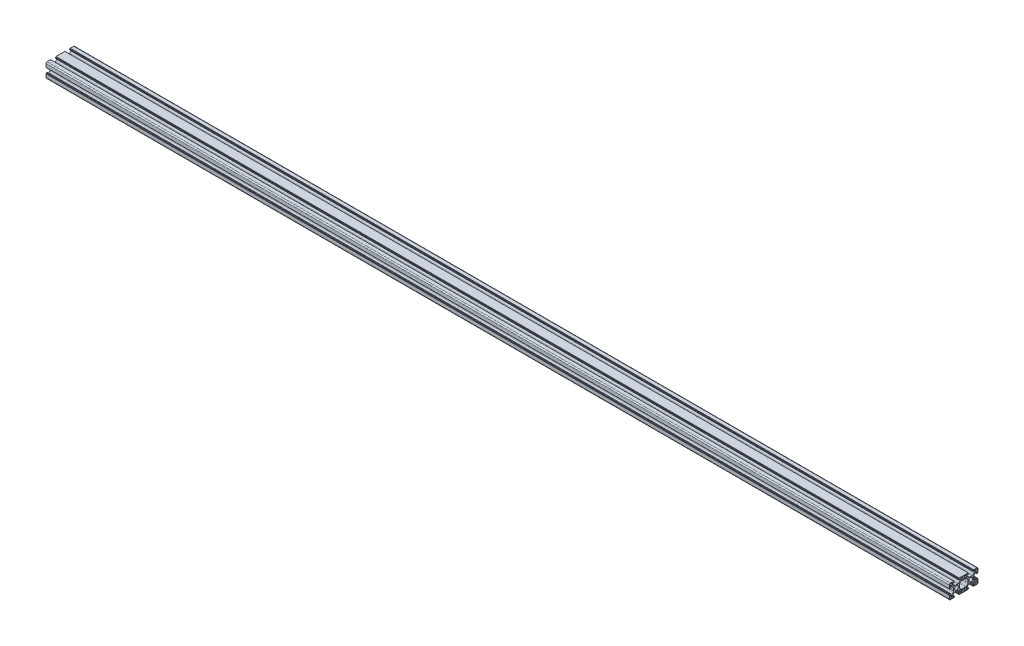
SolidWorks part; units mm, degrees
ref_plane "Спереди" through (0, 0, 0) normal (0, 0, 1) x (1, 0, 0)
ref_plane "Сверху" through (0, 0, 0) normal (0, 1, 0) x (1, 0, 0)
ref_plane "Справа" through (0, 0, 0) normal (1, 0, 0) x (0, 0, -1)
sketch "Эскиз1" plane through (0, 0, 0) normal (1, 0, 0) x (0, 0, -1)
  line L0 (-3.1522, 8.2837) -> (-1.6522, 6.7837) construction
  line L1 (18.3478, 9.7837) -> (15.3478, 6.7837) construction
  line L2 (-10.7522, 0.6837) -> (-0.7522, 10.6837) construction
  line L3 (9.2478, 4.6837) -> (11.1466, 4.6837)
  line L4 (9.2478, 0.6837) -> (19.2478, 10.6837) construction
  line L5 (16.8478, 8.2837) -> (15.3478, 9.7837) construction
  line L6 (12.5608, 5.2695) -> (13.862, 6.5707)
  line L7 (16.1478, 6.7837) -> (17.5478, 6.7837)
  line L8 (15.3478, 7.5837) -> (15.3478, 8.9837)
  line L9 (17.5478, 9.7837) -> (16.1478, 9.7837)
  line L10 (14.4478, 8.8837) -> (14.4478, 7.9849)
  line L11 (13.011, 8.757) -> (13.4914, 9.2373)
  line L12 (12.4478, 10.2328) -> (12.9478, 10.2328)
  line L13 (12.8343, 8.6837) -> (12.5478, 8.6837)
  line L14 (13.8449, 9.3837) -> (13.9478, 9.3837)
  line L15 (12.9478, 10.5337) -> (12.9478, 10.2328)
  line L16 (12.2978, 10.0828) -> (12.2978, 8.9337)
  line L17 (17.7478, 10.6837) -> (13.0978, 10.6837)
  line L18 (18.3478, 8.9837) -> (18.3478, 7.5837)
  line L19 (19.2478, 9.1837) -> (19.2478, 4.5337)
  line L20 (18.6469, 3.7337) -> (17.4978, 3.7337)
  line L21 (19.0978, 4.3837) -> (18.7969, 4.3837)
  line L22 (17.9478, 5.2808) -> (17.9478, 5.3837)
  line L23 (17.2478, 4.2702) -> (17.2478, 3.9837)
  line L24 (18.7969, 3.8837) -> (18.7969, 4.3837)
  line L25 (17.321, 4.447) -> (17.8014, 4.9273)
  line L26 (17.4478, 5.8837) -> (16.549, 5.8837)
  line L27 (13.8336, 3.9967) -> (15.1348, 5.2979)
  line L28 (13.2478, 0.6837) -> (13.2478, 2.5825)
  line L29 (13.2478, 0.6837) -> (13.2478, -1.2151)
  line L30 (13.8336, -2.6293) -> (15.1348, -3.9305)
  line L31 (15.3478, -6.2163) -> (15.3478, -7.6163)
  line L32 (16.1478, -5.4163) -> (17.5478, -5.4163)
  line L33 (18.3478, -7.6163) -> (18.3478, -6.2163)
  line L34 (17.4478, -4.5163) -> (16.549, -4.5163)
  line L35 (17.321, -3.0795) -> (17.8014, -3.5598)
  line L36 (18.7969, -2.5163) -> (18.7969, -3.0163)
  line L37 (17.2478, -2.9027) -> (17.2478, -2.6163)
  line L38 (17.9478, -3.9134) -> (17.9478, -4.0163)
  line L39 (19.0978, -3.0163) -> (18.7969, -3.0163)
  line L40 (18.6469, -2.3663) -> (17.4978, -2.3663)
  line L41 (19.2478, -7.8163) -> (19.2478, -3.1663)
  line L42 (17.5478, -8.4163) -> (16.1478, -8.4163)
  line L43 (17.7478, -9.3163) -> (13.0978, -9.3163)
  line L44 (12.2978, -8.7153) -> (12.2978, -7.5663)
  line L45 (12.9478, -9.1663) -> (12.9478, -8.8653)
  line L46 (13.8449, -8.0163) -> (13.9478, -8.0163)
  line L47 (12.8343, -7.3163) -> (12.5478, -7.3163)
  line L48 (12.4478, -8.8653) -> (12.9478, -8.8653)
  line L49 (13.011, -7.3895) -> (13.4914, -7.8698)
  line L50 (14.4478, -7.5163) -> (14.4478, -6.6175)
  line L51 (12.5608, -3.9021) -> (13.862, -5.2033)
  line L52 (9.2478, -3.3163) -> (11.1466, -3.3163)
  line L53 (18.3478, -8.4163) -> (15.3478, -5.4163) construction
  line L54 (9.2478, 0.6837) -> (19.2478, -9.3163) construction
  line L55 (16.8478, -6.9163) -> (18.3478, -5.4163) construction
  line L56 (9.2478, -3.3163) -> (7.349, -3.3163)
  line L57 (5.9348, -3.9021) -> (4.6336, -5.2033)
  line L58 (2.3478, -5.4163) -> (0.9478, -5.4163)
  line L59 (3.1478, -6.2163) -> (3.1478, -7.6163)
  line L60 (0.9478, -8.4163) -> (2.3478, -8.4163)
  line L61 (4.0478, -7.5163) -> (4.0478, -6.6175)
  line L62 (5.4846, -7.3895) -> (5.0043, -7.8698)
  line L63 (6.0478, -8.8653) -> (5.5478, -8.8653)
  line L64 (5.6614, -7.3163) -> (5.9478, -7.3163)
  line L65 (4.6507, -8.0163) -> (4.5478, -8.0163)
  line L66 (5.5478, -9.1663) -> (5.5478, -8.8653)
  line L67 (6.1978, -8.7153) -> (6.1978, -7.5663)
  line L68 (0.7478, -9.3163) -> (5.3978, -9.3163)
  line L69 (0.1478, -7.6163) -> (0.1478, -6.2163)
  line L70 (1.0478, -4.5163) -> (1.9466, -4.5163)
  line L71 (4.662, -2.6293) -> (3.3608, -3.9305)
  line L72 (5.2478, 0.6837) -> (5.2478, -1.2151)
  line L73 (-1.6522, 9.7837) -> (-4.6522, 6.7837) construction
  line L74 (0.1478, -8.4163) -> (3.1478, -5.4163) construction
  line L75 (-3.1522, -6.9163) -> (-4.6522, -8.4163) construction
  line L76 (9.2478, 0.6837) -> (-0.7522, -9.3163) construction
  line L77 (1.6478, -6.9163) -> (3.1478, -8.4163) construction
  line L78 (5.2478, 0.6837) -> (5.2478, 2.5825)
  line L79 (4.662, 3.9967) -> (3.3608, 5.2979)
  line L80 (3.1478, 7.5837) -> (3.1478, 8.9837)
  line L81 (2.3478, 6.7837) -> (0.9478, 6.7837)
  line L82 (0.1478, 8.9837) -> (0.1478, 7.5837)
  line L83 (1.0478, 5.8837) -> (1.9466, 5.8837)
  line L84 (0.9478, 9.7837) -> (2.3478, 9.7837)
  line L85 (0.7478, 10.6837) -> (5.3978, 10.6837)
  line L86 (6.1978, 10.0828) -> (6.1978, 8.9337)
  line L87 (5.5478, 10.5337) -> (5.5478, 10.2328)
  line L88 (4.6507, 9.3837) -> (4.5478, 9.3837)
  line L89 (5.6614, 8.6837) -> (5.9478, 8.6837)
  line L90 (6.0478, 10.2328) -> (5.5478, 10.2328)
  line L91 (5.4846, 8.757) -> (5.0043, 9.2373)
  line L92 (4.0478, 8.8837) -> (4.0478, 7.9849)
  line L93 (5.9348, 5.2695) -> (4.6336, 6.5707)
  line L94 (9.2478, 4.6837) -> (7.349, 4.6837)
  line L95 (-2.5162, 0.6837) -> (20.7522, 0.6837) construction
  line L96 (0.1478, 9.7837) -> (3.1478, 6.7837) construction
  line L97 (9.2478, -11.4027) -> (9.2478, 11.4027) construction
  line L98 (9.2478, 0.6837) -> (-0.7522, 10.6837) construction
  line L99 (1.6478, 8.2837) -> (0.1478, 6.7837) construction
  line L100 (-10.7522, 0.6837) -> (-0.7522, -9.3163) construction
  line L101 (-1.6522, -8.4163) -> (-4.6522, -5.4163) construction
  line L102 (-18.3522, -6.9163) -> (-19.8522, -5.4163) construction
  line L103 (-10.7522, 0.6837) -> (-20.7522, -9.3163) construction
  line L104 (-19.8522, -8.4163) -> (-16.8522, -5.4163) construction
  line L105 (-18.3522, 8.2837) -> (-16.8522, 9.7837) construction
  line L106 (-10.7522, 0.6837) -> (-20.7522, 10.6837) construction
  line L107 (-19.8522, 9.7837) -> (-16.8522, 6.7837) construction
  line L108 (-10.7522, 4.6837) -> (-8.8534, 4.6837)
  line L109 (-7.4392, 5.2695) -> (-6.138, 6.5707)
  line L110 (-5.5522, 8.8837) -> (-5.5522, 7.9849)
  line L111 (-6.989, 8.757) -> (-6.5086, 9.2373)
  line L112 (-7.5522, 10.2328) -> (-7.0522, 10.2328)
  line L113 (-7.1657, 8.6837) -> (-7.4522, 8.6837)
  line L114 (-6.1551, 9.3837) -> (-6.0522, 9.3837)
  line L115 (-7.0522, 10.5337) -> (-7.0522, 10.2328)
  line L116 (-7.7022, 10.0828) -> (-7.7022, 8.9337)
  line L117 (-2.2522, 10.6837) -> (-6.9022, 10.6837)
  line L118 (-2.4522, 9.7837) -> (-3.8522, 9.7837)
  line L119 (-2.5522, 5.8837) -> (-3.451, 5.8837)
  line L120 (-1.6522, 8.9837) -> (-1.6522, 7.5837)
  line L121 (-3.8522, 6.7837) -> (-2.4522, 6.7837)
  line L122 (-4.6522, 7.5837) -> (-4.6522, 8.9837)
  line L123 (-6.1664, 3.9967) -> (-4.8652, 5.2979)
  line L124 (-6.7522, 0.6837) -> (-6.7522, 2.5825)
  line L125 (-6.7522, 0.6837) -> (-6.7522, -1.2151)
  line L126 (-6.1664, -2.6293) -> (-4.8652, -3.9305)
  line L127 (-2.5522, -4.5163) -> (-3.451, -4.5163)
  line L128 (-1.6522, -7.6163) -> (-1.6522, -6.2163)
  line L129 (-2.2522, -9.3163) -> (-6.9022, -9.3163)
  line L130 (-7.7022, -8.7153) -> (-7.7022, -7.5663)
  line L131 (-7.0522, -9.1663) -> (-7.0522, -8.8653)
  line L132 (-6.1551, -8.0163) -> (-6.0522, -8.0163)
  line L133 (-7.1657, -7.3163) -> (-7.4522, -7.3163)
  line L134 (-7.5522, -8.8653) -> (-7.0522, -8.8653)
  line L135 (-6.989, -7.3895) -> (-6.5086, -7.8698)
  line L136 (-5.5522, -7.5163) -> (-5.5522, -6.6175)
  line L137 (-2.4522, -8.4163) -> (-3.8522, -8.4163)
  line L138 (-4.6522, -6.2163) -> (-4.6522, -7.6163)
  line L139 (-3.8522, -5.4163) -> (-2.4522, -5.4163)
  line L140 (-7.4392, -3.9021) -> (-6.138, -5.2033)
  line L141 (-10.7522, -3.3163) -> (-8.8534, -3.3163)
  line L142 (-10.7522, -3.3163) -> (-12.651, -3.3163)
  line L143 (-14.0652, -3.9021) -> (-15.3664, -5.2033)
  line L144 (-15.9522, -7.5163) -> (-15.9522, -6.6175)
  line L145 (-14.5154, -7.3895) -> (-14.9957, -7.8698)
  line L146 (-13.9522, -8.8653) -> (-14.4522, -8.8653)
  line L147 (-14.3386, -7.3163) -> (-14.0522, -7.3163)
  line L148 (-15.3493, -8.0163) -> (-15.4522, -8.0163)
  line L149 (-14.4522, -9.1663) -> (-14.4522, -8.8653)
  line L150 (-13.8022, -8.7153) -> (-13.8022, -7.5663)
  line L151 (-19.2522, -9.3163) -> (-14.6022, -9.3163)
  line L152 (-19.0522, -8.4163) -> (-17.6522, -8.4163)
  line L153 (-20.7522, -7.8163) -> (-20.7522, -3.1663)
  line L154 (-20.1512, -2.3663) -> (-19.0022, -2.3663)
  line L155 (-20.6022, -3.0163) -> (-20.3012, -3.0163)
  line L156 (-19.4522, -3.9134) -> (-19.4522, -4.0163)
  line L157 (-18.7522, -2.9027) -> (-18.7522, -2.6163)
  line L158 (-20.3012, -2.5163) -> (-20.3012, -3.0163)
  line L159 (-18.8254, -3.0795) -> (-19.3057, -3.5598)
  line L160 (-18.9522, -4.5163) -> (-18.0534, -4.5163)
  line L161 (-19.8522, -7.6163) -> (-19.8522, -6.2163)
  line L162 (-17.6522, -5.4163) -> (-19.0522, -5.4163)
  line L163 (-16.8522, -6.2163) -> (-16.8522, -7.6163)
  line L164 (-15.338, -2.6293) -> (-16.6392, -3.9305)
  line L165 (-14.7522, 0.6837) -> (-14.7522, -1.2151)
  line L166 (-14.7522, 0.6837) -> (-14.7522, 2.5825)
  line L167 (-15.338, 3.9967) -> (-16.6392, 5.2979)
  line L168 (-18.9522, 5.8837) -> (-18.0534, 5.8837)
  line L169 (-18.8254, 4.447) -> (-19.3057, 4.9273)
  line L170 (-20.3012, 3.8837) -> (-20.3012, 4.3837)
  line L171 (-18.7522, 4.2702) -> (-18.7522, 3.9837)
  line L172 (-19.4522, 5.2808) -> (-19.4522, 5.3837)
  line L173 (-20.6022, 4.3837) -> (-20.3012, 4.3837)
  line L174 (-20.1512, 3.7337) -> (-19.0022, 3.7337)
  line L175 (-20.7522, 9.1837) -> (-20.7522, 4.5337)
  line L176 (-19.8522, 8.9837) -> (-19.8522, 7.5837)
  line L177 (-19.2522, 10.6837) -> (-14.6022, 10.6837)
  line L178 (-13.8022, 10.0828) -> (-13.8022, 8.9337)
  line L179 (-14.4522, 10.5337) -> (-14.4522, 10.2328)
  line L180 (-15.3493, 9.3837) -> (-15.4522, 9.3837)
  line L181 (-14.3386, 8.6837) -> (-14.0522, 8.6837)
  line L182 (-13.9522, 10.2328) -> (-14.4522, 10.2328)
  line L183 (-14.5154, 8.757) -> (-14.9957, 9.2373)
  line L184 (-15.9522, 8.8837) -> (-15.9522, 7.9849)
  line L185 (-19.0522, 9.7837) -> (-17.6522, 9.7837)
  line L186 (-16.8522, 7.5837) -> (-16.8522, 8.9837)
  line L187 (-17.6522, 6.7837) -> (-19.0522, 6.7837)
  line L188 (-14.0652, 5.2695) -> (-15.3664, 6.5707)
  line L189 (-10.7522, 4.6837) -> (-12.651, 4.6837)
  line L190 (-2.2522, -9.3163) -> (0.7478, -9.3163)
  line L191 (-2.5522, -4.5163) -> (1.0478, -4.5163)
  line L192 (-2.5522, 5.8837) -> (1.0478, 5.8837)
  line L193 (-2.2522, 10.6837) -> (0.7478, 10.6837)
  arc A0 (18.3478, 8.9837) -> (17.5478, 9.7837) centre (17.5478, 8.9837) ccw
  arc A1 (16.1478, 9.7837) -> (15.3478, 8.9837) centre (16.1478, 8.9837) ccw
  arc A2 (16.1478, 6.7837) -> (15.3478, 7.5837) centre (16.1478, 7.5837) cw
  arc A3 (17.7478, 10.6837) -> (19.2478, 9.1837) centre (17.7478, 9.1837) cw
  arc A4 (12.4478, 10.2328) -> (12.2978, 10.0828) centre (12.4478, 10.0828) ccw
  arc A5 (13.0978, 10.6837) -> (12.9478, 10.5337) centre (13.0978, 10.5337) ccw
  arc A6 (12.8343, 8.6837) -> (13.011, 8.757) centre (12.8343, 8.9337) ccw
  arc A7 (12.5478, 8.6837) -> (12.2978, 8.9337) centre (12.5478, 8.9337) cw
  arc A8 (13.4914, 9.2373) -> (13.8449, 9.3837) centre (13.8449, 8.8837) cw
  arc A9 (13.9478, 9.3837) -> (14.4478, 8.8837) centre (13.9478, 8.8837) cw
  arc A10 (11.7478, 0.6837) -> (9.2478, 3.1837) centre (9.2478, 0.6837) ccw
  arc A11 (11.1466, 4.6837) -> (12.5608, 5.2695) centre (11.1466, 6.6837) ccw
  arc A12 (14.4478, 7.9849) -> (13.862, 6.5707) centre (12.4478, 7.9849) cw
  arc A13 (18.3478, 7.5837) -> (17.5478, 6.7837) centre (17.5478, 7.5837) cw
  arc A14 (17.9478, 5.3837) -> (17.4478, 5.8837) centre (17.4478, 5.3837) ccw
  arc A15 (17.8014, 4.9273) -> (17.9478, 5.2808) centre (17.4478, 5.2808) ccw
  arc A16 (17.2478, 3.9837) -> (17.4978, 3.7337) centre (17.4978, 3.9837) ccw
  arc A17 (17.2478, 4.2702) -> (17.321, 4.447) centre (17.4978, 4.2702) cw
  arc A18 (19.2478, 4.5337) -> (19.0978, 4.3837) centre (19.0978, 4.5337) cw
  arc A19 (18.7969, 3.8837) -> (18.6469, 3.7337) centre (18.6469, 3.8837) cw
  arc A20 (16.549, 5.8837) -> (15.1348, 5.2979) centre (16.549, 3.8837) ccw
  arc A21 (13.2478, 2.5825) -> (13.8336, 3.9967) centre (15.2478, 2.5825) cw
  arc A22 (17.5478, -8.4163) -> (18.3478, -7.6163) centre (17.5478, -7.6163) ccw
  arc A23 (18.3478, -6.2163) -> (17.5478, -5.4163) centre (17.5478, -6.2163) ccw
  arc A24 (15.3478, -6.2163) -> (16.1478, -5.4163) centre (16.1478, -6.2163) cw
  arc A25 (19.2478, -7.8163) -> (17.7478, -9.3163) centre (17.7478, -7.8163) cw
  arc A26 (18.7969, -2.5163) -> (18.6469, -2.3663) centre (18.6469, -2.5163) ccw
  arc A27 (19.2478, -3.1663) -> (19.0978, -3.0163) centre (19.0978, -3.1663) ccw
  arc A28 (17.2478, -2.9027) -> (17.321, -3.0795) centre (17.4978, -2.9027) ccw
  arc A29 (17.2478, -2.6163) -> (17.4978, -2.3663) centre (17.4978, -2.6163) cw
  arc A30 (17.8014, -3.5598) -> (17.9478, -3.9134) centre (17.4478, -3.9134) cw
  arc A31 (17.9478, -4.0163) -> (17.4478, -4.5163) centre (17.4478, -4.0163) cw
  arc A32 (9.2478, -1.8163) -> (11.7478, 0.6837) centre (9.2478, 0.6837) ccw
  arc A33 (13.2478, -1.2151) -> (13.8336, -2.6293) centre (15.2478, -1.2151) ccw
  arc A34 (16.549, -4.5163) -> (15.1348, -3.9305) centre (16.549, -2.5163) cw
  arc A35 (16.1478, -8.4163) -> (15.3478, -7.6163) centre (16.1478, -7.6163) cw
  arc A36 (13.9478, -8.0163) -> (14.4478, -7.5163) centre (13.9478, -7.5163) ccw
  arc A37 (13.4914, -7.8698) -> (13.8449, -8.0163) centre (13.8449, -7.5163) ccw
  arc A38 (12.5478, -7.3163) -> (12.2978, -7.5663) centre (12.5478, -7.5663) ccw
  arc A39 (12.8343, -7.3163) -> (13.011, -7.3895) centre (12.8343, -7.5663) cw
  arc A40 (13.0978, -9.3163) -> (12.9478, -9.1663) centre (13.0978, -9.1663) cw
  arc A41 (12.4478, -8.8653) -> (12.2978, -8.7153) centre (12.4478, -8.7153) cw
  arc A42 (14.4478, -6.6175) -> (13.862, -5.2033) centre (12.4478, -6.6175) ccw
  arc A43 (11.1466, -3.3163) -> (12.5608, -3.9021) centre (11.1466, -5.3163) cw
  arc A44 (0.1478, -7.6163) -> (0.9478, -8.4163) centre (0.9478, -7.6163) ccw
  arc A45 (2.3478, -8.4163) -> (3.1478, -7.6163) centre (2.3478, -7.6163) ccw
  arc A46 (2.3478, -5.4163) -> (3.1478, -6.2163) centre (2.3478, -6.2163) cw
  arc A47 (6.0478, -8.8653) -> (6.1978, -8.7153) centre (6.0478, -8.7153) ccw
  arc A48 (5.3978, -9.3163) -> (5.5478, -9.1663) centre (5.3978, -9.1663) ccw
  arc A49 (5.6614, -7.3163) -> (5.4846, -7.3895) centre (5.6614, -7.5663) ccw
  arc A50 (5.9478, -7.3163) -> (6.1978, -7.5663) centre (5.9478, -7.5663) cw
  arc A51 (5.0043, -7.8698) -> (4.6507, -8.0163) centre (4.6507, -7.5163) cw
  arc A52 (4.5478, -8.0163) -> (4.0478, -7.5163) centre (4.5478, -7.5163) cw
  arc A53 (6.7478, 0.6837) -> (9.2478, -1.8163) centre (9.2478, 0.6837) ccw
  arc A54 (7.349, -3.3163) -> (5.9348, -3.9021) centre (7.349, -5.3163) ccw
  arc A55 (4.0478, -6.6175) -> (4.6336, -5.2033) centre (6.0478, -6.6175) cw
  arc A56 (0.1478, -6.2163) -> (0.9478, -5.4163) centre (0.9478, -6.2163) cw
  arc A57 (1.9466, -4.5163) -> (3.3608, -3.9305) centre (1.9466, -2.5163) ccw
  arc A58 (5.2478, -1.2151) -> (4.662, -2.6293) centre (3.2478, -1.2151) cw
  arc A59 (0.9478, 9.7837) -> (0.1478, 8.9837) centre (0.9478, 8.9837) ccw
  arc A60 (0.1478, 7.5837) -> (0.9478, 6.7837) centre (0.9478, 7.5837) ccw
  arc A61 (3.1478, 7.5837) -> (2.3478, 6.7837) centre (2.3478, 7.5837) cw
  arc A62 (9.2478, 3.1837) -> (6.7478, 0.6837) centre (9.2478, 0.6837) ccw
  arc A63 (5.2478, 2.5825) -> (4.662, 3.9967) centre (3.2478, 2.5825) ccw
  arc A64 (1.9466, 5.8837) -> (3.3608, 5.2979) centre (1.9466, 3.8837) cw
  arc A65 (2.3478, 9.7837) -> (3.1478, 8.9837) centre (2.3478, 8.9837) cw
  arc A66 (4.5478, 9.3837) -> (4.0478, 8.8837) centre (4.5478, 8.8837) ccw
  arc A67 (5.0043, 9.2373) -> (4.6507, 9.3837) centre (4.6507, 8.8837) ccw
  arc A68 (5.9478, 8.6837) -> (6.1978, 8.9337) centre (5.9478, 8.9337) ccw
  arc A69 (5.6614, 8.6837) -> (5.4846, 8.757) centre (5.6614, 8.9337) cw
  arc A70 (5.3978, 10.6837) -> (5.5478, 10.5337) centre (5.3978, 10.5337) cw
  arc A71 (6.0478, 10.2328) -> (6.1978, 10.0828) centre (6.0478, 10.0828) cw
  arc A72 (4.0478, 7.9849) -> (4.6336, 6.5707) centre (6.0478, 7.9849) ccw
  arc A73 (7.349, 4.6837) -> (5.9348, 5.2695) centre (7.349, 6.6837) cw
  arc A74 (-8.8534, 4.6837) -> (-7.4392, 5.2695) centre (-8.8534, 6.6837) ccw
  arc A75 (-5.5522, 7.9849) -> (-6.138, 6.5707) centre (-7.5522, 7.9849) cw
  arc A76 (-7.5522, 10.2328) -> (-7.7022, 10.0828) centre (-7.5522, 10.0828) ccw
  arc A77 (-6.9022, 10.6837) -> (-7.0522, 10.5337) centre (-6.9022, 10.5337) ccw
  arc A78 (-7.1657, 8.6837) -> (-6.989, 8.757) centre (-7.1657, 8.9337) ccw
  arc A79 (-7.4522, 8.6837) -> (-7.7022, 8.9337) centre (-7.4522, 8.9337) cw
  arc A80 (-6.5086, 9.2373) -> (-6.1551, 9.3837) centre (-6.1551, 8.8837) cw
  arc A81 (-6.0522, 9.3837) -> (-5.5522, 8.8837) centre (-6.0522, 8.8837) cw
  arc A82 (-3.8522, 9.7837) -> (-4.6522, 8.9837) centre (-3.8522, 8.9837) ccw
  arc A83 (-3.451, 5.8837) -> (-4.8652, 5.2979) centre (-3.451, 3.8837) ccw
  arc A84 (-6.7522, 2.5825) -> (-6.1664, 3.9967) centre (-4.7522, 2.5825) cw
  arc A85 (-10.7522, 3.1837) -> (-8.2522, 0.6837) centre (-10.7522, 0.6837) cw
  arc A86 (-4.6522, 7.5837) -> (-3.8522, 6.7837) centre (-3.8522, 7.5837) ccw
  arc A87 (-1.6522, 7.5837) -> (-2.4522, 6.7837) centre (-2.4522, 7.5837) cw
  arc A88 (-2.4522, 9.7837) -> (-1.6522, 8.9837) centre (-2.4522, 8.9837) cw
  arc A89 (-6.7522, -1.2151) -> (-6.1664, -2.6293) centre (-4.7522, -1.2151) ccw
  arc A90 (-3.451, -4.5163) -> (-4.8652, -3.9305) centre (-3.451, -2.5163) cw
  arc A91 (-1.6522, -6.2163) -> (-2.4522, -5.4163) centre (-2.4522, -6.2163) ccw
  arc A92 (-5.5522, -6.6175) -> (-6.138, -5.2033) centre (-7.5522, -6.6175) ccw
  arc A93 (-8.8534, -3.3163) -> (-7.4392, -3.9021) centre (-8.8534, -5.3163) cw
  arc A94 (-8.2522, 0.6837) -> (-10.7522, -1.8163) centre (-10.7522, 0.6837) cw
  arc A95 (-6.0522, -8.0163) -> (-5.5522, -7.5163) centre (-6.0522, -7.5163) ccw
  arc A96 (-6.5086, -7.8698) -> (-6.1551, -8.0163) centre (-6.1551, -7.5163) ccw
  arc A97 (-7.4522, -7.3163) -> (-7.7022, -7.5663) centre (-7.4522, -7.5663) ccw
  arc A98 (-7.1657, -7.3163) -> (-6.989, -7.3895) centre (-7.1657, -7.5663) cw
  arc A99 (-6.9022, -9.3163) -> (-7.0522, -9.1663) centre (-6.9022, -9.1663) cw
  arc A100 (-7.5522, -8.8653) -> (-7.7022, -8.7153) centre (-7.5522, -8.7153) cw
  arc A101 (-3.8522, -5.4163) -> (-4.6522, -6.2163) centre (-3.8522, -6.2163) ccw
  arc A102 (-3.8522, -8.4163) -> (-4.6522, -7.6163) centre (-3.8522, -7.6163) cw
  arc A103 (-1.6522, -7.6163) -> (-2.4522, -8.4163) centre (-2.4522, -7.6163) cw
  arc A104 (-12.651, -3.3163) -> (-14.0652, -3.9021) centre (-12.651, -5.3163) ccw
  arc A105 (-15.9522, -6.6175) -> (-15.3664, -5.2033) centre (-13.9522, -6.6175) cw
  arc A106 (-13.9522, -8.8653) -> (-13.8022, -8.7153) centre (-13.9522, -8.7153) ccw
  arc A107 (-14.6022, -9.3163) -> (-14.4522, -9.1663) centre (-14.6022, -9.1663) ccw
  arc A108 (-14.3386, -7.3163) -> (-14.5154, -7.3895) centre (-14.3386, -7.5663) ccw
  arc A109 (-14.0522, -7.3163) -> (-13.8022, -7.5663) centre (-14.0522, -7.5663) cw
  arc A110 (-14.9957, -7.8698) -> (-15.3493, -8.0163) centre (-15.3493, -7.5163) cw
  arc A111 (-15.4522, -8.0163) -> (-15.9522, -7.5163) centre (-15.4522, -7.5163) cw
  arc A112 (-17.6522, -8.4163) -> (-16.8522, -7.6163) centre (-17.6522, -7.6163) ccw
  arc A113 (-18.0534, -4.5163) -> (-16.6392, -3.9305) centre (-18.0534, -2.5163) ccw
  arc A114 (-14.7522, -1.2151) -> (-15.338, -2.6293) centre (-16.7522, -1.2151) cw
  arc A115 (-10.7522, -1.8163) -> (-13.2522, 0.6837) centre (-10.7522, 0.6837) cw
  arc A116 (-19.4522, -4.0163) -> (-18.9522, -4.5163) centre (-18.9522, -4.0163) ccw
  arc A117 (-19.3057, -3.5598) -> (-19.4522, -3.9134) centre (-18.9522, -3.9134) ccw
  arc A118 (-18.7522, -2.6163) -> (-19.0022, -2.3663) centre (-19.0022, -2.6163) ccw
  arc A119 (-18.7522, -2.9027) -> (-18.8254, -3.0795) centre (-19.0022, -2.9027) cw
  arc A120 (-20.7522, -3.1663) -> (-20.6022, -3.0163) centre (-20.6022, -3.1663) cw
  arc A121 (-20.3012, -2.5163) -> (-20.1512, -2.3663) centre (-20.1512, -2.5163) cw
  arc A122 (-20.7522, -7.8163) -> (-19.2522, -9.3163) centre (-19.2522, -7.8163) ccw
  arc A123 (-16.8522, -6.2163) -> (-17.6522, -5.4163) centre (-17.6522, -6.2163) ccw
  arc A124 (-19.8522, -6.2163) -> (-19.0522, -5.4163) centre (-19.0522, -6.2163) cw
  arc A125 (-19.0522, -8.4163) -> (-19.8522, -7.6163) centre (-19.0522, -7.6163) cw
  arc A126 (-14.7522, 2.5825) -> (-15.338, 3.9967) centre (-16.7522, 2.5825) ccw
  arc A127 (-18.0534, 5.8837) -> (-16.6392, 5.2979) centre (-18.0534, 3.8837) cw
  arc A128 (-20.3012, 3.8837) -> (-20.1512, 3.7337) centre (-20.1512, 3.8837) ccw
  arc A129 (-20.7522, 4.5337) -> (-20.6022, 4.3837) centre (-20.6022, 4.5337) ccw
  arc A130 (-18.7522, 4.2702) -> (-18.8254, 4.447) centre (-19.0022, 4.2702) ccw
  arc A131 (-18.7522, 3.9837) -> (-19.0022, 3.7337) centre (-19.0022, 3.9837) cw
  arc A132 (-19.3057, 4.9273) -> (-19.4522, 5.2808) centre (-18.9522, 5.2808) cw
  arc A133 (-19.4522, 5.3837) -> (-18.9522, 5.8837) centre (-18.9522, 5.3837) cw
  arc A134 (-19.8522, 7.5837) -> (-19.0522, 6.7837) centre (-19.0522, 7.5837) ccw
  arc A135 (-15.9522, 7.9849) -> (-15.3664, 6.5707) centre (-13.9522, 7.9849) ccw
  arc A136 (-12.651, 4.6837) -> (-14.0652, 5.2695) centre (-12.651, 6.6837) cw
  arc A137 (-13.2522, 0.6837) -> (-10.7522, 3.1837) centre (-10.7522, 0.6837) cw
  arc A138 (-15.4522, 9.3837) -> (-15.9522, 8.8837) centre (-15.4522, 8.8837) ccw
  arc A139 (-14.9957, 9.2373) -> (-15.3493, 9.3837) centre (-15.3493, 8.8837) ccw
  arc A140 (-14.0522, 8.6837) -> (-13.8022, 8.9337) centre (-14.0522, 8.9337) ccw
  arc A141 (-14.3386, 8.6837) -> (-14.5154, 8.757) centre (-14.3386, 8.9337) cw
  arc A142 (-14.6022, 10.6837) -> (-14.4522, 10.5337) centre (-14.6022, 10.5337) cw
  arc A143 (-13.9522, 10.2328) -> (-13.8022, 10.0828) centre (-13.9522, 10.0828) cw
  arc A144 (-19.2522, 10.6837) -> (-20.7522, 9.1837) centre (-19.2522, 9.1837) ccw
  arc A145 (-17.6522, 6.7837) -> (-16.8522, 7.5837) centre (-17.6522, 7.5837) ccw
  arc A146 (-17.6522, 9.7837) -> (-16.8522, 8.9837) centre (-17.6522, 8.9837) cw
  arc A147 (-19.8522, 8.9837) -> (-19.0522, 9.7837) centre (-19.0522, 8.9837) cw
  point P0 (9.2478, 0.6837)
  point P12 (9.2478, 0.6837)
  point P45 (17.9478, 4.3837)
  point P104 (12.9478, -8.0163)
  point P155 (12.9478, 9.3837)
  point P163 (17.9478, -3.0163)
  point P164 (9.2478, -3.2405)
  point P166 (9.2478, 0.6837)
  point P224 (5.5478, -8.0163)
  point P225 (5.3236, 0.6837)
  point P227 (9.2478, 0.6837)
  point P267 (5.5478, 9.3837)
  point P272 (13.1721, 0.6837)
  point P288 (9.2478, 4.608)
  point P290 (9.2478, 0.6837)
  point P515 (-10.7522, 4.608)
  point P516 (-14.6764, 0.6837)
  point P517 (-7.0522, 9.3837)
  point P518 (-6.8279, 0.6837)
  point P519 (-7.0522, -8.0163)
  point P520 (-10.7522, -3.2405)
  point P521 (-19.4522, -3.0163)
  point P522 (-14.4522, 9.3837)
  point P523 (-14.4522, -8.0163)
  point P524 (-19.4522, 4.3837)
  dimension "D3" = 5
  dimension "D6" = 2
  dimension "D1" = 2
  dimension "D2" = 6
  dimension "D4" = 4
  dimension "D5" = 0.9
extrude "Бобышка-Вытянуть1" add sketch "Эскиз1" along normal blind 1260
